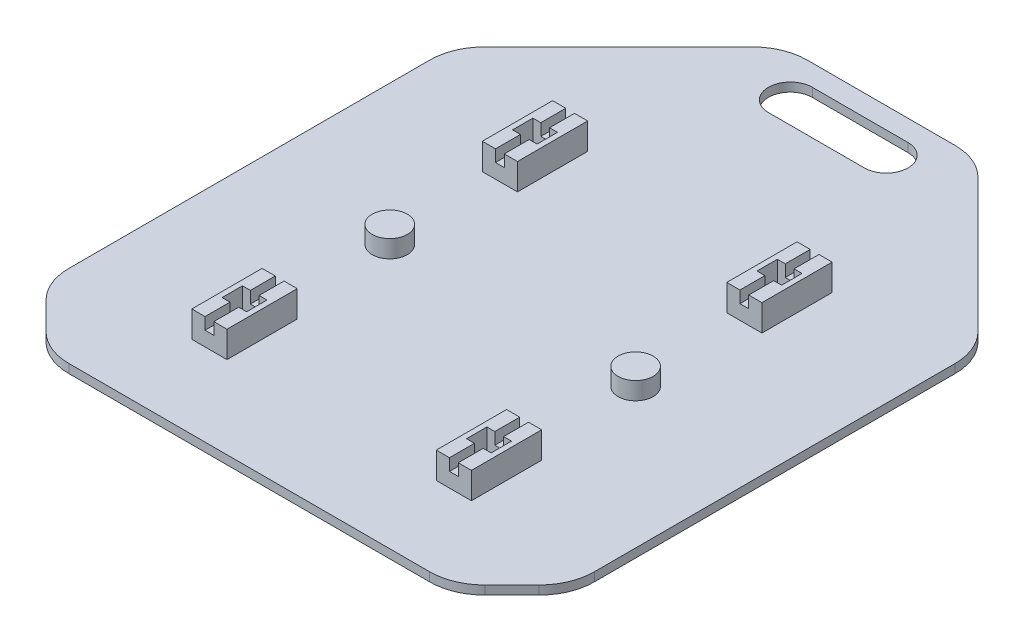
SolidWorks part; units mm, degrees
ref_plane "Front Plane" through (0, 0, 0) normal (0, 0, 1) x (1, 0, 0)
ref_plane "Top Plane" through (0, 0, 0) normal (0, 1, 0) x (1, 0, 0)
ref_plane "Right Plane" through (0, 0, 0) normal (1, 0, 0) x (0, 0, -1)
sketch "Sketch1" plane through (0, 0, 0) normal (0, 1, 0) x (1, 0, 0)
  line L0 (0, 0) -> (294, 0)
  line L1 (294, 0) -> (336.996, 43.004)
  line L2 (336.996, 43.004) -> (336.996, 337.004)
  line L3 (336.996, 337.004) -> (217, 457)
  line L4 (217, 457) -> (77, 457)
  line L5 (77, 457) -> (-42.996, 337.004)
  line L6 (-42.996, 337.004) -> (-42.996, 43.004)
  line L7 (-42.996, 43.004) -> (0, 0)
  dimension "D1" = 294
  dimension "D2" = 294
  dimension "D3" = 457
  dimension "D5" = 60.8112
  dimension "D7" = 169.7
  dimension "D9" = 225
  dimension "D10" = 140
extrude "Body" add sketch "Sketch1" along normal blind 6.35
sketch "Sketch2" plane through (0, 6.35, 0) normal (0, 1, 0) x (1, 0, 0)
  line L3 (217, 457) -> (77, 457) construction
  line L4 (112.35, 441.8) -> (181.65, 441.8)
  line L5 (112.35, 441.8) -> (112.35, 410.1)
  line L6 (112.35, 410.1) -> (181.65, 410.1)
  line L7 (181.65, 441.8) -> (181.65, 410.1)
  line L8 (217, 457) -> (77, 457)
  arc A1 (112.35, 441.8) -> (112.35, 410.1) centre (112.35, 425.95) ccw
  arc A2 (181.65, 441.8) -> (181.65, 410.1) centre (181.65, 425.95) cw
  point P8 (147, 410.1)
  point P9 (147, 457)
  dimension "D3" = 15.85
  dimension "D4" = 15.2
  dimension "D1" = 69.3
  dimension "D2" = 31.7
extrude "Handle" cut sketch "Sketch2" against normal blind 6.35 contours L6 A2 L4 A1
fillet "Fillet1" radius 40 2 edges at (217, 3.175, -457) (77, 3.175, -457)
fillet "Fillet2" radius 40 6 edges at (-42.996, 3.175, -337.004) (-42.996, 3.175, -43.004) (0, 3.175, 0) (294, 3.175, 0) (336.996, 3.175, -43.004) (336.996, 3.175, -337.004)
sketch "Sketch3" plane through (0, 6.35, 0) normal (0, 1, 0) x (1, 0, 0)
  line L0 (147, 410.1) -> (147, 0) construction
  line L1 (112.35, 410.1) -> (181.65, 410.1) construction
  line L2 (16.5707, 0) -> (277.4293, 0) construction
  line L3 (248.096, 269.6354) -> (222.696, 269.6354)
  line L4 (45.904, 320.4354) -> (71.304, 320.4354)
  line L5 (45.904, 320.4354) -> (45.904, 269.6354)
  line L6 (45.904, 269.6354) -> (71.304, 269.6354)
  line L7 (71.304, 320.4354) -> (71.304, 269.6354)
  line L8 (222.696, 320.4354) -> (222.696, 269.6354)
  line L9 (248.096, 320.4354) -> (222.696, 320.4354)
  line L10 (248.096, 320.4354) -> (248.096, 269.6354)
  line L11 (65.2843, 445.2843) -> (-31.2803, 348.7197)
  line L12 (-42.996, 320.4354) -> (-42.996, 59.5704)
  line L13 (-31.2829, 31.2887) -> (-11.7162, 11.7183)
  line L14 (16.5707, 0) -> (277.4293, 0)
  line L15 (305.7162, 11.7183) -> (325.2829, 31.2887)
  line L16 (336.996, 59.5704) -> (336.996, 320.4354)
  line L17 (325.2803, 348.7197) -> (228.7157, 445.2843)
  line L18 (200.4315, 457) -> (93.5685, 457)
  line L19 (65.2843, 445.2843) -> (-31.2803, 348.7197) construction
  line L20 (-42.996, 320.4354) -> (-42.996, 59.5704) construction
  line L21 (-31.2829, 31.2887) -> (-11.7162, 11.7183) construction
  line L22 (16.5707, 0) -> (277.4293, 0) construction
  line L23 (305.7162, 11.7183) -> (325.2829, 31.2887) construction
  line L24 (336.996, 59.5704) -> (336.996, 320.4354) construction
  line L25 (325.2803, 348.7197) -> (228.7157, 445.2843) construction
  line L26 (200.4315, 457) -> (93.5685, 457) construction
  line L27 (-42.996, 190.0029) -> (336.996, 190.0029) construction
  line L28 (248.096, 59.5704) -> (248.096, 110.3704)
  line L29 (248.096, 59.5704) -> (222.696, 59.5704)
  line L30 (222.696, 59.5704) -> (222.696, 110.3704)
  line L31 (248.096, 110.3704) -> (222.696, 110.3704)
  line L32 (45.904, 110.3704) -> (71.304, 110.3704)
  line L33 (71.304, 59.5704) -> (71.304, 110.3704)
  line L34 (45.904, 59.5704) -> (71.304, 59.5704)
  line L35 (45.904, 59.5704) -> (45.904, 110.3704)
  arc A8 (-31.2803, 348.7197) -> (-42.996, 320.4354) centre (-2.996, 320.4354) ccw
  arc A9 (-42.996, 59.5704) -> (-31.2829, 31.2887) centre (-2.996, 59.5704) ccw
  arc A10 (-11.7162, 11.7183) -> (16.5707, 0) centre (16.5707, 40) ccw
  arc A11 (277.4293, 0) -> (305.7162, 11.7183) centre (277.4293, 40) ccw
  arc A12 (325.2829, 31.2887) -> (336.996, 59.5704) centre (296.996, 59.5704) ccw
  arc A13 (336.996, 320.4354) -> (325.2803, 348.7197) centre (296.996, 320.4354) ccw
  arc A14 (228.7157, 445.2843) -> (200.4315, 457) centre (200.4315, 417) ccw
  arc A15 (93.5685, 457) -> (65.2843, 445.2843) centre (93.5685, 417) ccw
  arc A16 (-31.2803, 348.7197) -> (-42.996, 320.4354) centre (-2.996, 320.4354) ccw construction
  arc A17 (-42.996, 59.5704) -> (-31.2829, 31.2887) centre (-2.996, 59.5704) ccw construction
  arc A18 (-11.7162, 11.7183) -> (16.5707, 0) centre (16.5707, 40) ccw construction
  arc A19 (277.4293, 0) -> (305.7162, 11.7183) centre (277.4293, 40) ccw construction
  arc A20 (325.2829, 31.2887) -> (336.996, 59.5704) centre (296.996, 59.5704) ccw construction
  arc A21 (336.996, 320.4354) -> (325.2803, 348.7197) centre (296.996, 320.4354) ccw construction
  arc A22 (228.7157, 445.2843) -> (200.4315, 457) centre (200.4315, 417) ccw construction
  arc A23 (93.5685, 457) -> (65.2843, 445.2843) centre (93.5685, 417) ccw construction
  dimension "D2" = 25.4
  dimension "D3" = 50.8
  dimension "D4" = 88.9
  dimension "D1" = 0
extrude "Boss-Extrude2" add sketch "Sketch3" along normal blind 19.05 contours L4 L7 L6 L5 | L31 L30 L29 L28 | L32 L33 L34 L35 | L9 L8 L3 L10
sketch "Sketch4" plane through (0, 25.4, 0) normal (0, 1, 0) x (1, 0, 0)
  line L0 (147, 410.1) -> (147, 15.7137) construction
  line L1 (49.714, 302.4078) -> (67.494, 302.4078)
  line L2 (49.714, 302.4078) -> (49.714, 287.6631)
  line L3 (49.714, 287.6631) -> (67.494, 287.6631)
  line L4 (67.494, 302.4078) -> (67.494, 287.6631)
  line L5 (112.35, 410.1) -> (181.65, 410.1) construction
  line L7 (244.286, 287.6631) -> (226.506, 287.6631)
  line L8 (45.904, 320.4354) -> (45.904, 269.6354)
  line L9 (45.904, 269.6354) -> (71.304, 269.6354)
  line L10 (71.304, 269.6354) -> (71.304, 320.4354)
  line L11 (71.304, 320.4354) -> (45.904, 320.4354)
  line L12 (45.904, 320.4354) -> (45.904, 269.6354)
  line L13 (45.904, 269.6354) -> (71.304, 269.6354)
  line L14 (71.304, 269.6354) -> (71.304, 320.4354)
  line L15 (71.304, 320.4354) -> (45.904, 320.4354)
  line L16 (226.506, 302.4078) -> (226.506, 287.6631)
  line L17 (244.286, 302.4078) -> (226.506, 302.4078)
  line L18 (244.286, 302.4078) -> (244.286, 287.6631)
  line L19 (49.714, 92.3427) -> (67.494, 92.3427)
  line L20 (49.714, 92.3427) -> (49.714, 77.598)
  line L21 (49.714, 77.598) -> (67.494, 77.598)
  line L22 (67.494, 92.3427) -> (67.494, 77.598)
  line L23 (226.506, 92.3427) -> (244.286, 92.3427)
  line L24 (226.506, 92.3427) -> (226.506, 77.598)
  line L25 (226.506, 77.598) -> (244.286, 77.598)
  line L26 (244.286, 92.3427) -> (244.286, 77.598)
  line L27 (248.096, 59.5704) -> (248.096, 110.3704) construction
  line L28 (248.096, 110.3704) -> (222.696, 110.3704) construction
  line L29 (222.696, 110.3704) -> (222.696, 59.5704) construction
  line L30 (222.696, 59.5704) -> (248.096, 59.5704) construction
  line L31 (45.904, 110.3704) -> (45.904, 59.5704) construction
  line L32 (45.904, 59.5704) -> (71.304, 59.5704) construction
  line L33 (71.304, 59.5704) -> (71.304, 110.3704) construction
  line L34 (71.304, 110.3704) -> (45.904, 110.3704) construction
  line L35 (248.096, 59.5704) -> (248.096, 110.3704)
  line L36 (248.096, 110.3704) -> (222.696, 110.3704)
  line L37 (222.696, 110.3704) -> (222.696, 59.5704)
  line L38 (222.696, 59.5704) -> (248.096, 59.5704)
  line L39 (45.904, 110.3704) -> (45.904, 59.5704)
  line L40 (45.904, 59.5704) -> (71.304, 59.5704)
  line L41 (71.304, 59.5704) -> (71.304, 110.3704)
  line L42 (71.304, 110.3704) -> (45.904, 110.3704)
  point P6 (49.714, 295.0354)
  point P8 (45.904, 295.0354)
  point P10 (58.604, 302.4078)
  point P11 (58.604, 320.4354)
  point P26 (235.396, 110.3704)
  point P27 (58.604, 92.3427)
  point P30 (49.714, 84.9704)
  point P31 (235.396, 92.3427)
  point P34 (58.604, 110.3704)
  point P36 (244.286, 84.9704)
  point P38 (248.096, 84.9704)
  point P39 (45.904, 84.9704)
  dimension "D2" = 17.78
  dimension "D3" = 14.7447
  dimension "D4" = 17.78
  dimension "D5" = 14.7447
  dimension "D6" = 17.78
  dimension "D7" = 14.7447
  dimension "D1" = 0
extrude "Cut-Extrude1" cut sketch "Sketch4" against normal blind 17.78 contours L2 L3 L4 L1 | L24 L25 L26 L23 | L16 L7 L18 L17 | L20 L21 L22 L19
sketch "Sketch5" plane through (0, 25.4, 0) normal (0, 1, 0) x (1, 0, 0)
  line L0 (49.714, 302.4078) -> (49.714, 287.6631) construction
  line L5 (49.714, 302.4078) -> (49.714, 287.6631) construction
  line L6 (49.714, 302.4078) -> (67.494, 302.4078) construction
  line L7 (55.429, 110.3704) -> (61.779, 110.3704)
  line L8 (45.904, 320.4354) -> (45.904, 269.6354)
  line L9 (45.904, 269.6354) -> (71.304, 269.6354)
  line L10 (71.304, 269.6354) -> (71.304, 320.4354)
  line L11 (71.304, 320.4354) -> (45.904, 320.4354)
  line L12 (45.904, 320.4354) -> (45.904, 269.6354) construction
  line L13 (45.904, 269.6354) -> (71.304, 269.6354) construction
  line L14 (71.304, 269.6354) -> (71.304, 320.4354) construction
  line L15 (71.304, 320.4354) -> (45.904, 320.4354) construction
  line L20 (147, 410.1) -> (147, 255.7871) construction
  line L21 (112.35, 410.1) -> (181.65, 410.1) construction
  line L31 (55.429, 320.4354) -> (61.779, 320.4354)
  line L32 (55.429, 320.4354) -> (55.429, 302.4078)
  line L36 (49.714, 92.3427) -> (49.714, 77.598) construction
  line L37 (45.904, 59.5704) -> (45.904, 110.3704) construction
  line L38 (49.714, 92.3427) -> (49.714, 77.598) construction
  line L39 (45.904, 59.5704) -> (45.904, 110.3704) construction
  line L40 (55.429, 302.4078) -> (61.779, 302.4078)
  line L41 (61.779, 92.3427) -> (61.779, 110.3704)
  line L42 (55.429, 92.3427) -> (61.779, 92.3427)
  line L55 (61.779, 320.4354) -> (61.779, 302.4078)
  line L56 (49.714, 302.4078) -> (67.494, 302.4078) construction
  line L57 (49.714, 295.0354) -> (64.2871, 295.0354) construction
  line L58 (55.429, 287.6631) -> (61.779, 287.6631)
  line L59 (61.779, 269.6354) -> (61.779, 287.6631)
  line L60 (55.429, 269.6354) -> (61.779, 269.6354)
  line L61 (55.429, 269.6354) -> (55.429, 287.6631)
  line L62 (238.571, 269.6354) -> (238.571, 287.6631)
  line L63 (238.571, 269.6354) -> (232.221, 269.6354)
  line L64 (232.221, 269.6354) -> (232.221, 287.6631)
  line L65 (238.571, 287.6631) -> (232.221, 287.6631)
  line L66 (238.571, 302.4078) -> (232.221, 302.4078)
  line L67 (232.221, 320.4354) -> (232.221, 302.4078)
  line L68 (238.571, 320.4354) -> (232.221, 320.4354)
  line L69 (238.571, 320.4354) -> (238.571, 302.4078)
  line L70 (55.429, 92.3427) -> (55.429, 110.3704)
  line L71 (45.904, 110.3704) -> (71.304, 110.3704) construction
  line L72 (45.904, 110.3704) -> (71.304, 110.3704) construction
  line L73 (49.714, 84.9704) -> (62.1248, 84.9704) construction
  line L74 (55.429, 77.598) -> (55.429, 59.5704)
  line L75 (55.429, 77.598) -> (61.779, 77.598)
  line L76 (61.779, 77.598) -> (61.779, 59.5704)
  line L77 (55.429, 59.5704) -> (61.779, 59.5704)
  line L78 (238.571, 77.598) -> (232.221, 77.598)
  line L79 (232.221, 77.598) -> (232.221, 59.5704)
  line L80 (238.571, 59.5704) -> (232.221, 59.5704)
  line L81 (238.571, 77.598) -> (238.571, 59.5704)
  line L82 (238.571, 92.3427) -> (238.571, 110.3704)
  line L83 (238.571, 92.3427) -> (232.221, 92.3427)
  line L84 (232.221, 92.3427) -> (232.221, 110.3704)
  line L85 (238.571, 110.3704) -> (232.221, 110.3704)
  point P10 (58.604, 302.4078)
  point P13 (58.604, 302.4078)
  point P40 (58.604, 110.3704)
  point P43 (58.604, 110.3704)
  dimension "D2" = 6.35
  dimension "D1" = 0
extrude "Cut-Extrude2" cut sketch "Sketch5" against normal blind 8.5725
sketch "Sketch6" plane through (0, 6.35, 0) normal (0, 1, 0) x (1, 0, 0)
  line L3 (147, 0) -> (147, 410.1) construction
  line L4 (16.5707, 0) -> (277.4293, 0) construction
  line L5 (112.35, 410.1) -> (181.65, 410.1) construction
  circle A0 centre (58.1, 190.5) radius 12.7
  circle A1 centre (235.9, 190.5) radius 12.7
  dimension "D1" = 25.4
  dimension "D2" = 177.8
  dimension "D3" = 190.5
extrude "Boss-Extrude3" add sketch "Sketch6" along normal blind 12.7 contours A0 | A1
